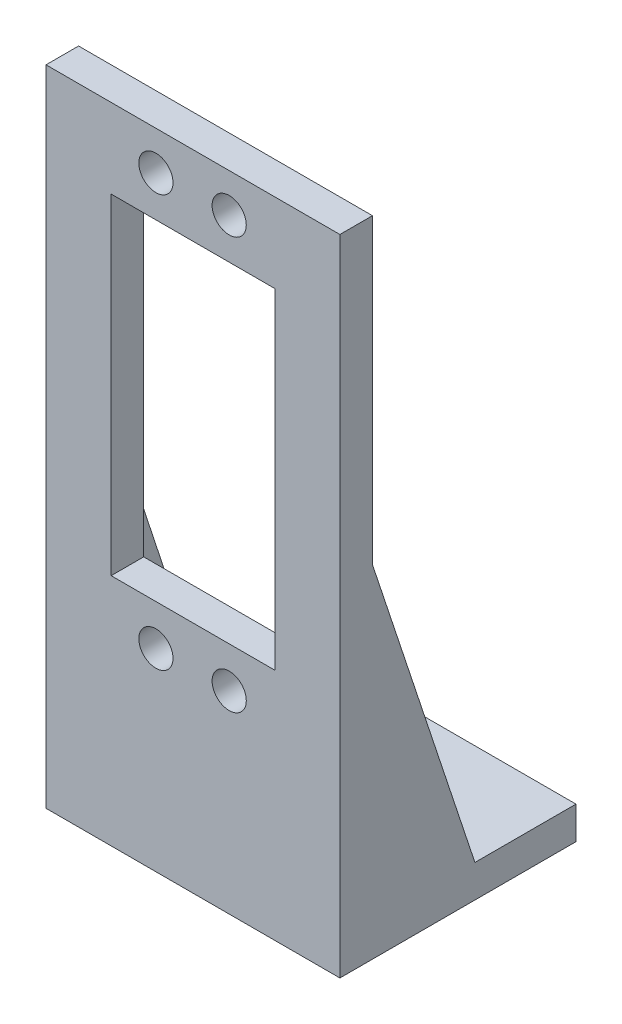
SolidWorks part; units mm, degrees
ref_plane "Front Plane" through (0, 0, 0) normal (0, 0, 1) x (1, 0, 0)
ref_plane "Top Plane" through (0, 0, 0) normal (0, 1, 0) x (1, 0, 0)
ref_plane "Right Plane" through (0, 0, 0) normal (1, 0, 0) x (0, 0, -1)
sketch "Sketch1" plane through (0, 0, 0) normal (0, 0, 1) x (1, 0, 0)
  line L0 (-20.1, 30.1) -> (16, 30.1)
  line L1 (-12.1, -20.25) -> (8, -20.25)
  line L2 (-12.1, -20.25) -> (-12.1, 20.35)
  line L3 (-12.1, 20.35) -> (8, 20.35)
  line L4 (8, -20.25) -> (8, 20.35)
  line L5 (16, -45) -> (-20.1, -45)
  line L8 (-20.1, 30.1) -> (-20.1, -45)
  line L10 (16, 30.1) -> (16, -45)
  point P0 (0, 0)
  point P6 (0, 0)
  dimension "D2" = 40.6
  dimension "D3" = 20.1
  dimension "D4" = 8
  dimension "D5" = 8
  dimension "D6" = 9.75
extrude "Boss-Extrude1" add sketch "Sketch1" along normal blind 4
sketch "Sketch3" plane through (0, 0, 4) normal (0, 0, 1) x (1, 0, 0)
  line L0 (16, -45) -> (16, 30.1) construction
  line L1 (-20.1, -45) -> (16, -45)
  line L2 (-20.1, -45) -> (-20.1, -49)
  line L3 (-20.1, -49) -> (16, -49)
  line L4 (16, -45) -> (16, -49)
  dimension "D1" = 4
extrude "Boss-Extrude3" add sketch "Sketch3" against normal blind 29
sketch "Sketch9" plane through (16, 0, 0) normal (1, 0, 0) x (0, 0, -1)
  line L0 (0, -7.0316) -> (12.5857, -45)
  line L1 (0, -45) -> (0, 30.1) construction
  line L2 (25, -45) -> (0, -45) construction
  line L3 (0, -7.0316) -> (0, -45)
  line L4 (0, -45) -> (12.5857, -45)
  dimension "D1" = 40
extrude "Boss-Extrude4" add sketch "Sketch9" against normal blind 4
sketch "Sketch11" plane through (-20.1, 0, 0) normal (-1, 0, 0) x (0, 0, 1)
  line L0 (-12.5, -45) -> (0, -7.0033)
  line L1 (-25, -45) -> (0, -45) construction
  line L2 (0, 30.1) -> (0, -45) construction
  line L3 (0, -7.0033) -> (0, -45)
  line L4 (0, -45) -> (-12.5, -45)
  dimension "D1" = 40
extrude "Boss-Extrude5" add sketch "Sketch11" against normal blind 4
sketch "Sketch12" plane through (0, -45, 0) normal (0, 1, 0) x (1, 0, 0)
  circle A3 centre (2.5797, 17.1225) radius 2
  circle A5 centre (-6.5515, 7.9352) radius 2
extrude "Cut-Extrude2" cut sketch "Sketch12" against normal blind 4
sketch "Sketch13" plane through (0, -49, 0) normal (0, -1, 0) x (1, 0, 0)
  line L3 (-2.05, -25) -> (-2.05, 4) construction
  line L4 (-20.1, -25) -> (16, -25) construction
  line L5 (-20.1, 4) -> (16, 4) construction
sketch "Sketch16" plane through (0, 0, 4) normal (0, 0, 1) x (1, 0, 0)
  line L2 (-12.1, 20.35) -> (-12.1, -20.25) construction
  line L4 (8, 20.35) -> (-12.1, 20.35) construction
  line L5 (-12.1, -20.25) -> (8, -20.25) construction
  circle A0 centre (-6.6, 25.35) radius 2.1
  circle A1 centre (2.4, 25.35) radius 2.1
  circle A2 centre (-6.6, -25.25) radius 2.1
  circle A3 centre (2.4, -25.25) radius 2.1
  point P14 (0, 0)
  dimension "D5" = 4.2
  dimension "D6" = 4.2
  dimension "D11" = 4.2
  dimension "D12" = 4.2
  dimension "D2" = 5.5
  dimension "D3" = 5
  dimension "D4" = 9
  dimension "D7" = 5.5
  dimension "D8" = 5
  dimension "D9" = 5
  dimension "D10" = 9
  dimension "D13" = 5
extrude "Cut-Extrude3" cut sketch "Sketch16" against normal through all
